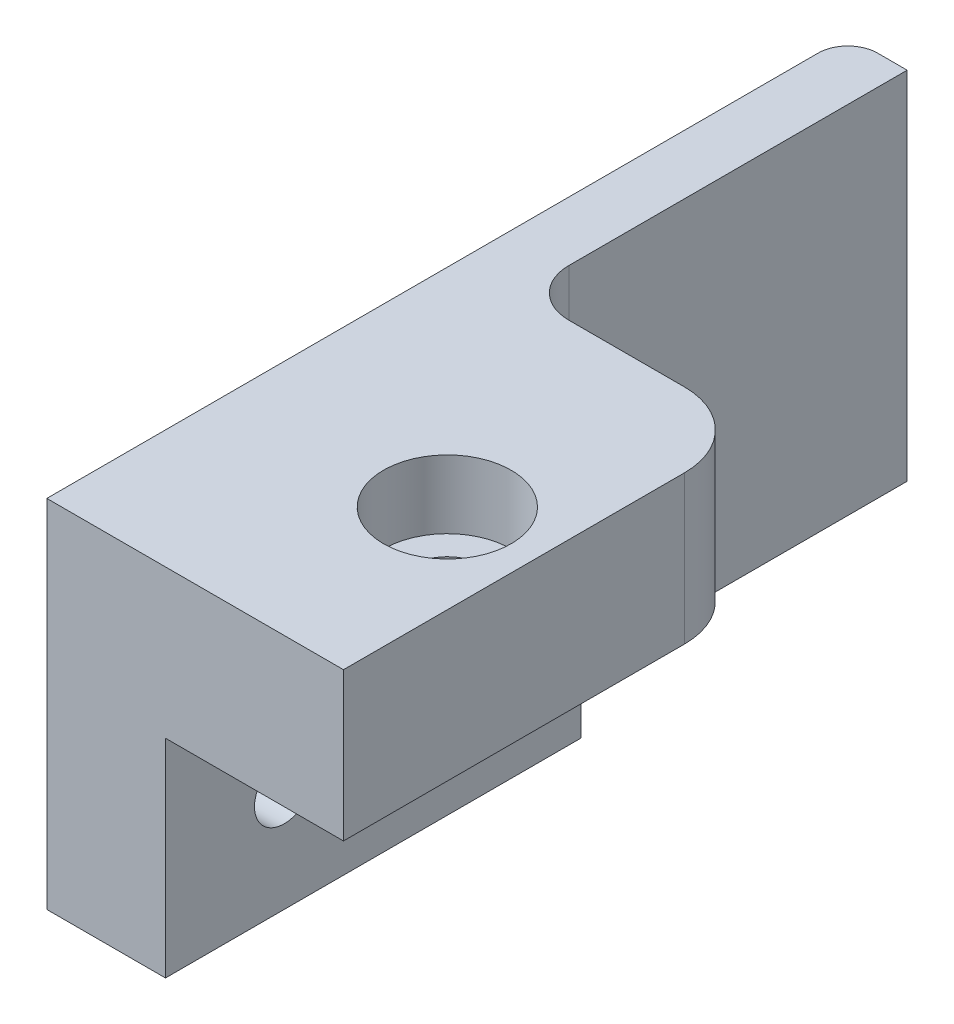
SolidWorks part; units mm, degrees
ref_plane "前视基准面" through (0, 0, 0) normal (0, 0, 1) x (1, 0, 0)
ref_plane "上视基准面" through (0, 0, 0) normal (0, 1, 0) x (1, 0, 0)
ref_plane "右视基准面" through (0, 0, 0) normal (1, 0, 0) x (0, 0, -1)
other "Configuration Table"
sketch "草图1" plane through (0, 0, 0) normal (0, 1, 0) x (1, 0, 0)
  line L1 (0, 81.7506) -> (0, -33.3911) construction
  line L2 (-67.2939, 0) -> (79.8315, 0) construction
  line L3 (3.6, 14) -> (7.5, 14)
  line L4 (1, 27) -> (2, 27)
  line L5 (10, 11.5) -> (10, 0)
  line L6 (2, 27) -> (2, 15.6)
  line L7 (0, 26) -> (0, 0)
  line L8 (0, 0) -> (10, 0)
  line L10 (2, 81.7506) -> (2, -33.3911) construction
  line L11 (10, 81.7506) -> (10, -33.3911) construction
  line L12 (-67.2939, 27) -> (79.8315, 27) construction
  line L13 (-67.2939, 14) -> (79.8315, 14) construction
  arc A0 (1, 27) -> (0, 26) centre (1, 26) ccw
  arc A1 (3.6, 14) -> (2, 15.6) centre (3.6, 15.6) cw
  arc A2 (10, 11.5) -> (7.5, 14) centre (7.5, 11.5) ccw
  point P19 (0, 27)
  dimension "D5" = 1
  dimension "D6" = 1.6
  dimension "D7" = 2.5
  dimension "D1" = 14
  dimension "D2" = 27
  dimension "D3" = 10
  dimension "D4" = 2
extrude "凸台-拉伸1" add sketch "草图1" along normal blind 12
sketch "草图2" plane through (0, 0, 0) normal (0, -1, 0) x (1, 0, 0)
  line L3 (4, 0) -> (10, 0)
  line L5 (4, -26) -> (4, 0)
  line L6 (4, -20) -> (4, 0)
  line L8 (0, -20) -> (10, -20)
  line L9 (4, -20) -> (10, -20)
  line L11 (10, -26) -> (10, 0)
  line L12 (10, -20) -> (10, 0)
  dimension "D2" = 4
  dimension "D3" = 20
  dimension "D4" = 10
extrude "切除-拉伸1" cut sketch "草图2" against normal blind 7
sketch "草图3" plane through (0, 0, 0) normal (-1, 0, 0) x (0, 0, 1)
  line L2 (-26, 3.5) -> (0, 3.5)
  line L3 (-26, 3.5) -> (0, 3.5) construction
  line L5 (-4, 12) -> (-4, 0)
  line L6 (-4, 12) -> (-4, 0) construction
  line L8 (-9, 12) -> (-9, 0)
  line L9 (-9, 12) -> (-9, 0) construction
  point P10 (-9, 3.5)
  point P12 (-4, 3.5)
  dimension "D1" = 3.5
  dimension "D2" = 4
  dimension "D3" = 9
hole_wizard "Ø2.0mm 暗销孔1" positions "草图3" profile "草图4" hole size "Ø2.0" standard "GB" end condition up to next
sketch "草图4" plane through (0, 3.5, -4) normal (0, 1, 0) x (0, 0, 1)
  line L0 (0, 0) -> (0, 4)
  line L1 (0, 4) -> (1, 4)
  line L2 (1, 4) -> (1, 0)
  line L5 (1, 0) -> (0, 0)
  line L11 (0, -6.35) -> (0, 107.95) construction
  dimension "通孔孔直径" = 2
  dimension "通孔孔深度" = 4
sketch "草图5" plane through (0, 12, 0) normal (0, 1, 0) x (1, 0, 0)
  line L2 (7, 0) -> (7, 11.5)
  line L3 (7, 0) -> (7, 12.3027) construction
  line L5 (0, 6.5) -> (10, 6.5)
  line L6 (0, 6.5) -> (10, 6.5) construction
  point P0 (7, 6.5)
  point P12 (0, 0)
  point P13 (0, 0)
  dimension "D1" = 3
  dimension "D2" = 6.5
hole_wizard "M2 六角圆柱头螺钉的柱形沉头孔1" positions "草图5" profile "草图6" counterbore size "M2" standard "GB" end condition up to next
sketch "草图6" plane through (7, 12, -6.5) normal (1, 0, 0) x (0, 0, 1)
  line L0 (0, 0) -> (0, 5)
  line L1 (0, 5) -> (1.2, 5)
  line L3 (1.2, 5) -> (1.2, 2.3)
  line L4 (1.2, 2.3) -> (2.15, 2.3)
  line L5 (2.15, 2.3) -> (2.15, 0)
  line L7 (2.15, 0) -> (0, 0)
  line L11 (0, -6.35) -> (0, 107.95) construction
  dimension "通孔孔直径" = 2.4
  dimension "通孔孔深度" = 5
  dimension "柱形沉头孔直径" = 4.3
  dimension "柱形沉头孔深度" = 2.3
